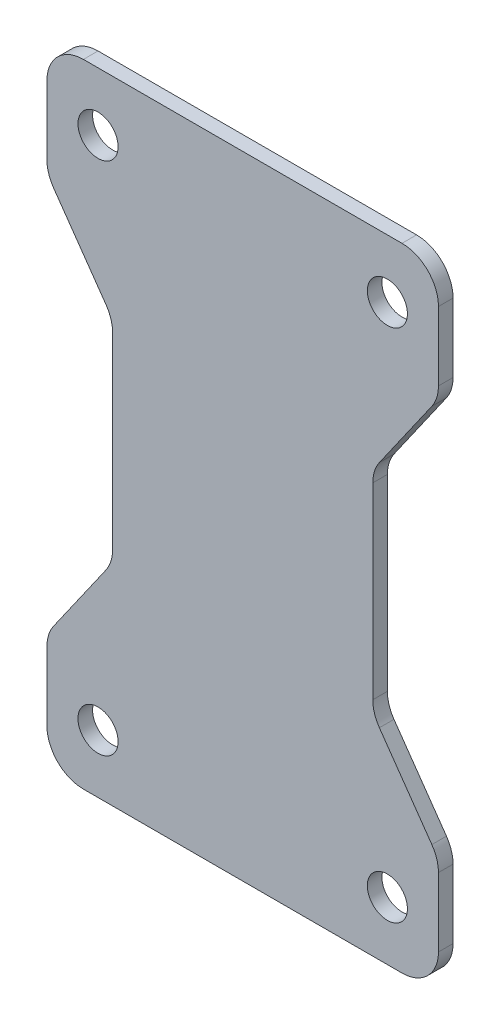
SolidWorks part; units mm, degrees
material "6061 Alloy"
ref_plane "Front Plane" through (0, 0, 0) normal (0, 0, 1) x (1, 0, 0)
ref_plane "Top Plane" through (0, 0, 0) normal (0, 1, 0) x (1, 0, 0)
ref_plane "Right Plane" through (0, 0, 0) normal (1, 0, 0) x (0, 0, -1)
sketch "Sketch11" plane through (0, 0, 0) normal (0, 0, 1) x (1, 0, 0)
  line L0 (0, 0) -> (0, 109.6398) construction
  line L1 (0, 0) -> (-89.1372, 0) construction
sketch "Sketch12" plane through (0, 0, 0) normal (0, 0, 1) x (1, 0, 0)
  line L0 (-25.65, 0) -> (-25.65, 203.2)
  line L1 (200000, 0) -> (-200089.1372, 0) construction
  line L4 (-21.0787, 0) -> (-25.65, 0)
  line L5 (-21.0787, 0) -> (-21.0787, 203.2)
  line L10 (-21.0787, 203.2) -> (-25.65, 203.2)
  line L13 (-21.0787, 203.2) -> (0, 203.2) construction
  line L14 (0, 203.2) -> (0, 0) construction
  line L15 (0, 0) -> (-21.0787, 0) construction
  point P4 (-21.0787, 205.2361)
  point P12 (-25.4, 0)
  dimension "D5" = 203.2
  dimension "D6" = 4.5713
  dimension "D1" = 51.3
  dimension "D2" = 42.1573
  dimension "D8" = 50.8
  dimension "D9" = 0.25
revolve "Revolve1" add sketch "Sketch12" angle 360 about L0
ref_plane "mideplane" through (0, 101.6, 0) normal (0, -1, 0) x (-1, 0, 0)
ref_plane "top pipe plane" through (0, 30, 0) normal (0, -1, 0) x (-1, 0, 0)
ref_plane "bottom pipe plane" through (0, 203.2, 0) normal (0, 1, 0) x (1, 0, 0)
ref_plane "pipe support midplane" through (0, 116.6, 0) normal (0, -1, 0) x (-1, 0, 0)
sketch "Sketch14" plane through (0, 30, 0) normal (0, -1, 0) x (-1, 0, 0)
  line L0 (0, 0) -> (-25.65, 0) construction
  line L1 (0, 0) -> (25.65, 0) construction
  line L7 (-25.65, -25.65) -> (25.65, -25.65)
  line L9 (25.65, -25.65) -> (25.65, 0)
  line L10 (-25.65, -25.65) -> (-25.65, 0)
  circle A0 centre (0, 0) radius 25.65 construction
  circle A1 centre (0, 0) radius 25.65
  circle A2 centre (0, 0) radius 25.65 construction
  arc A3 (25.65, 0) -> (-25.65, 0) centre (0, 0) cw
  dimension "D1" = 0
  dimension "D2" = 0
extrude "Boss-Extrude1" add sketch "Sketch14" against normal up to surface (173.2 mm away) contours A1 L10 L7 L9 | A1 L7 L9
sketch "Sketch27" plane through (0, 0, 25.65) normal (0, 0, 1) x (1, 0, 0)
  line L0 (25.65, 30) -> (53.65, 30)
  line L1 (53.65, 30) -> (53.65, 62)
  line L2 (53.65, 62) -> (35.65, 87.7067)
  line L3 (35.65, 87.7067) -> (35.65, 145.4933)
  line L4 (35.65, 145.4933) -> (53.65, 171.2)
  line L5 (25.65, 30) -> (25.65, 203.2)
  line L6 (25.65, 203.2) -> (-25.65, 203.2)
  line L8 (-25.65, 203.2) -> (-25.65, 30)
  line L9 (0, 30) -> (25.65, 30)
  line L10 (25.65, 30) -> (25.65, 203.2) construction
  line L11 (25.65, 203.2) -> (-25.65, 203.2)
  line L14 (0, 30) -> (25.65, 30)
  line L15 (53.65, 171.2) -> (53.65, 203.2)
  line L16 (25.65, 203.2) -> (53.65, 203.2)
  line L17 (53.65, 62) -> (25.65, 62) construction
  line L18 (25.65, 62) -> (53.65, 30) construction
  line L19 (53.65, 171.2) -> (25.65, 171.2) construction
  line L20 (25.65, 171.2) -> (53.65, 203.2) construction
  line L30 (-25.65, 203.2) -> (-25.65, 30)
  line L31 (-25.65, 30) -> (0, 30)
  line L32 (-25.65, 30) -> (0, 30)
  circle A0 centre (39.65, 46) radius 6 construction
  point P14 (39.65, 187.2)
  dimension "D2" = 12
  dimension "D3" = 10
  dimension "D6" = 8
  dimension "D4" = 10
  dimension "D5" = 55
  dimension "D1" = 0
extrude "Boss-Extrude2" add sketch "Sketch27" along normal blind 4 separate body
hole_wizard "M10 Clearance Hole1" positions "Sketch28" profile "Sketch29" hole size "M10" standard "ISO" end condition through all
sketch "Sketch28" plane through (0, 0, 25.65) normal (0, 0, -1) x (-1, 0, 0)
  point P0 (-39.65, 46)
  point P3 (-39.65, 187.2)
sketch "Sketch29" plane through (39.65, 46, 25.65) normal (1, 0, 0) x (0, 1, 0)
  line L0 (0, 0) -> (0, 4)
  line L1 (0, 4) -> (5.5, 4)
  line L2 (5.5, 4) -> (5.5, 0)
  line L5 (5.5, 0) -> (0, 0)
  line L11 (0, -6.35) -> (0, 107.95) construction
  dimension "Thru Hole Dia." = 11
  dimension "Thru Hole Depth" = 4
fillet "Fillet1" radius 10 6 edges at (53.65, 203.2, 27.65) (53.65, 171.2, 27.65) (35.65, 145.4933, 27.65) (35.65, 87.7067, 27.65) (53.65, 62, 27.65) (53.65, 30, 27.65)
mirror "Mirror1" about plane through (0, 0, 0) normal (1, 0, 0) of "Boss-Extrude2", "M10 Clearance Hole1", "Fillet1"
delete or keep bodies "Body-Delete/Keep 1" type delete bodies bodies 123
equation "\"bearing_bore\"= 1 + 21 / 32in"
equation "\"bearing_bore_max\"= 1.6568in"
equation "\"bearing_bore_min\"= 1.6558in"
equation "\"shaft_dia\"= 1.5in"
equation "\"shaft_dia_min\"= 1.51in"
equation "\"D2@Sketch12\"=\"bearing_bore_min\"+0.1mm"
equation "\"bearing_flange_diameter\"= 2in"
equation "\"bearing_flange_thickness\"= 0.078in"
equation "\"bearing_length\"= 1.5in"
equation "\"D8@Sketch12\"=\"bearing_flange_diameter\""
equation "\"nub_dia\"= 0.5in"
equation "\"D1@Sketch12\"= \"bearing_flange_diameter\" + 0.5"
